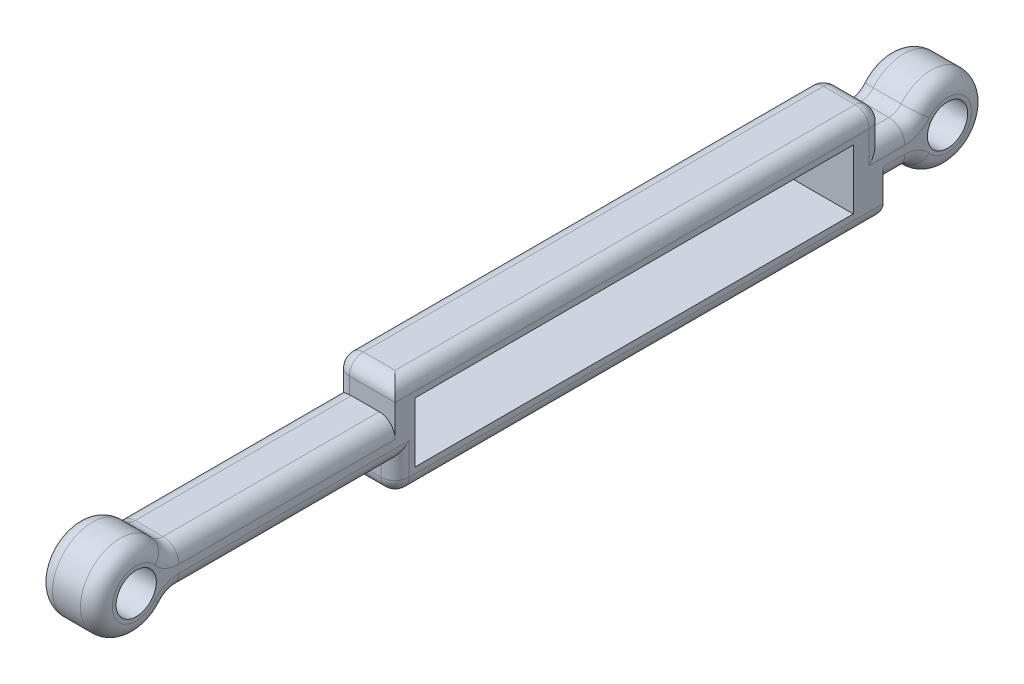
SolidWorks part; units mm, degrees
ref_plane "Front Plane" through (0, 0, 0) normal (0, 0, 1) x (1, 0, 0)
ref_plane "Top Plane" through (0, 0, 0) normal (0, 1, 0) x (1, 0, 0)
ref_plane "Right Plane" through (0, 0, 0) normal (1, 0, 0) x (0, 0, -1)
sketch "Sketch1" plane through (0, 0, 0) normal (1, 0, 0) x (0, 0, -1)
  line L1 (-140, 0) -> (0, 0) construction
  line L3 (-122.6795, 10) -> (-10, 10)
  line L4 (-122.6795, -10) -> (-10, -10)
  line L6 (0, 0) -> (267.3205, 0) construction
  line L7 (0, 55) -> (0, -55) construction
  line L8 (0, -15) -> (0, 15)
  line L9 (-10, 10) -> (-10, 25)
  line L10 (-10, 25) -> (235, 25)
  line L11 (0, 15) -> (220, 15)
  line L12 (0, -15) -> (220, -15)
  line L13 (-10, -10) -> (-10, -25)
  line L14 (-10, -25) -> (235, -25)
  line L15 (220, -15) -> (220, 15)
  line L16 (267.3205, 0) -> (267.3205, 10) construction
  line L17 (267.3205, 10) -> (250, 10) construction
  line L18 (267.3205, 0) -> (267.3205, -10) construction
  line L19 (267.3205, -10) -> (250, -10) construction
  line L20 (235, 25) -> (235, 10)
  line L21 (235, 10) -> (250, 10)
  line L22 (235, -25) -> (235, -10)
  line L23 (235, -10) -> (250, -10)
  arc A2 (-122.6795, 10) -> (-122.6795, -10) centre (-140, 0) ccw
  arc A3 (250, -10) -> (250, 10) centre (267.3205, 0) ccw
  point P5 (-70, 0)
  point P12 (0, 0)
  dimension "D1" = 140
  dimension "D2" = 20
  dimension "D10" = 220
  dimension "D14" = 20
  dimension "D3" = 20
  dimension "D4" = 10
  dimension "D5" = 10
  dimension "D6" = 30
  dimension "D7" = 10
  dimension "D8" = 10
  dimension "D9" = 112.6795
  dimension "D11" = 245
  dimension "D12" = 245
  dimension "D13" = 15
  dimension "D15" = 15
  dimension "D16" = 15
extrude "Boss-Extrude1" add sketch "Sketch1" along normal blind 30
sketch "Sketch2" plane through (0, 0, 0) normal (1, 0, 0) x (0, 0, -1)
  circle A0 centre (-140, 0) radius 10.1
  dimension "D1" = 20.2
extrude "Cut-Extrude1" cut sketch "Sketch2" along normal blind 30
sketch "Sketch3" plane through (0, 0, 0) normal (-1, 0, 0) x (0, 0, 1)
  circle A0 centre (-267.3205, 0) radius 10.1
  dimension "D1" = 20.2
extrude "Cut-Extrude2" cut sketch "Sketch3" against normal blind 30
fillet "Fillet1" radius 8 8 edges at (30, 10, 66.3397) (0, 10, 66.3397) (30, -10, 66.3397) (0, -10, 66.3397) (15, 10, 122.6795) (30, 0, 160) (15, -10, 122.6795) (0, 0, 160)
fillet "Fillet2" radius 8 8 edges at (30, -10, -242.5) (0, -10, -242.5) (30, 10, -242.5) (0, 10, -242.5) (15, -10, -250) (30, 0, -287.3205) (15, 10, -250) (0, 0, -287.3205)
fillet "Fillet4" radius 7 12 edges at (15, -25, 10) (30, -25, -112.5) (15, -25, -235) (0, -25, -112.5) (15, 25, -235) (30, 25, -112.5) (15, 25, 10) (0, 25, -112.5) (30, 13.5, -235) (0, 13.5, -235) (0, 13.5, 10) (30, -13.5, 10)
scale "Scale1" scale about origin uniform scaling yes scale factor 0.5
